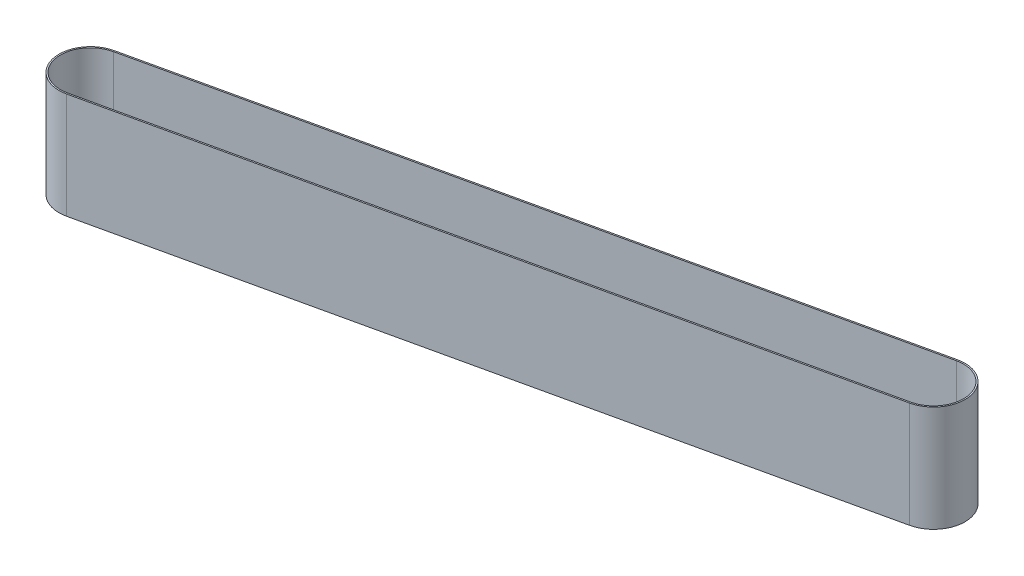
SolidWorks part; units mm, degrees
material "天然橡胶"
ref_plane "前视基准面" through (0, 0, 0) normal (0, 0, 1) x (1, 0, 0)
ref_plane "上视基准面" through (0, 0, 0) normal (0, 1, 0) x (1, 0, 0)
ref_plane "右视基准面" through (0, 0, 0) normal (1, 0, 0) x (0, 0, -1)
sketch "草图1" plane through (0, 0, 0) normal (0, 1, 0) x (1, 0, 0)
  line L0 (-152.7686, -20.6218) -> (823.2102, 197.2439)
  line L1 (841.7632, 114.1316) -> (-134.2156, -103.7341)
  line L2 (-153.2043, -18.6698) -> (822.7745, 199.1959)
  line L3 (842.1989, 112.1797) -> (-133.7798, -105.6861)
  arc A0 (-134.2156, -103.7341) -> (-152.7686, -20.6218) centre (-143.4921, -62.178) cw
  arc A1 (823.2102, 197.2439) -> (841.7632, 114.1316) centre (832.4867, 155.6878) cw
  arc A2 (822.7745, 199.1959) -> (842.1989, 112.1797) centre (832.4867, 155.6878) cw
  arc A3 (-133.7798, -105.6861) -> (-153.2043, -18.6698) centre (-143.4921, -62.178) cw
  dimension "D2" = 1000
  dimension "D1" = 2
extrude "凸台-拉伸1" add sketch "草图1" along normal blind 150
